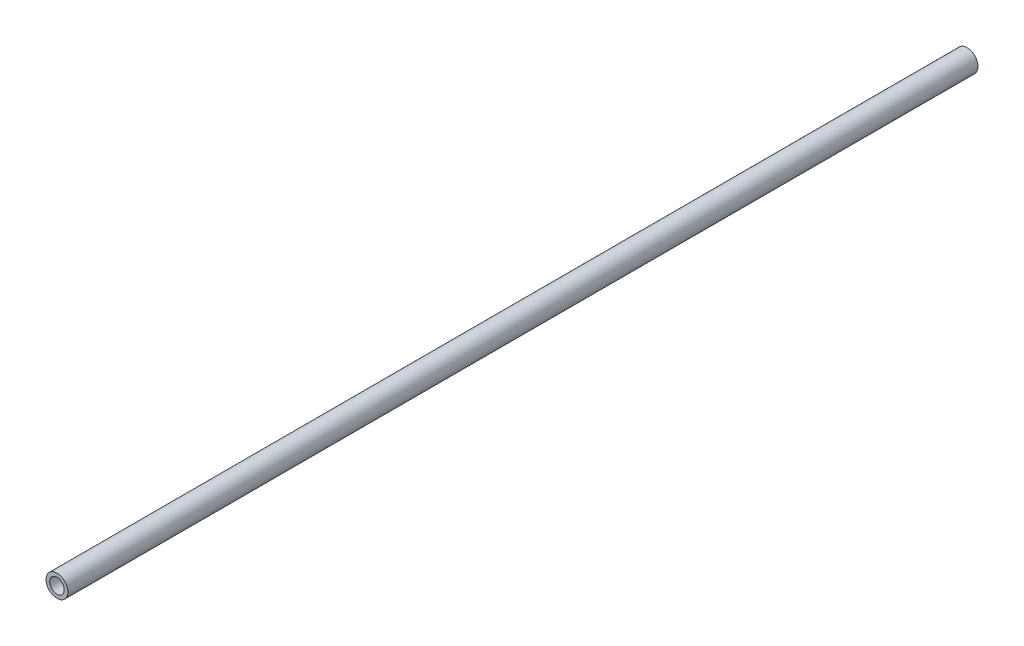
SolidWorks part; units mm, degrees
material "Alliage 1060"
ref_plane "Front" through (0, 0, 0) normal (0, 0, 1) x (1, 0, 0)
ref_plane "Top" through (0, 0, 0) normal (0, 1, 0) x (1, 0, 0)
ref_plane "Right" through (0, 0, 0) normal (1, 0, 0) x (0, 0, -1)
sketch "Esquisse1" plane through (0, 0, 0) normal (0, 0, 1) x (1, 0, 0)
  circle A0 centre (0, 0) radius 3
  dimension "D1" = 6
extrude "Extru.-Mince1" add sketch "Esquisse1" along normal blind 249.5 thin thin type one direction reverse wall 1
